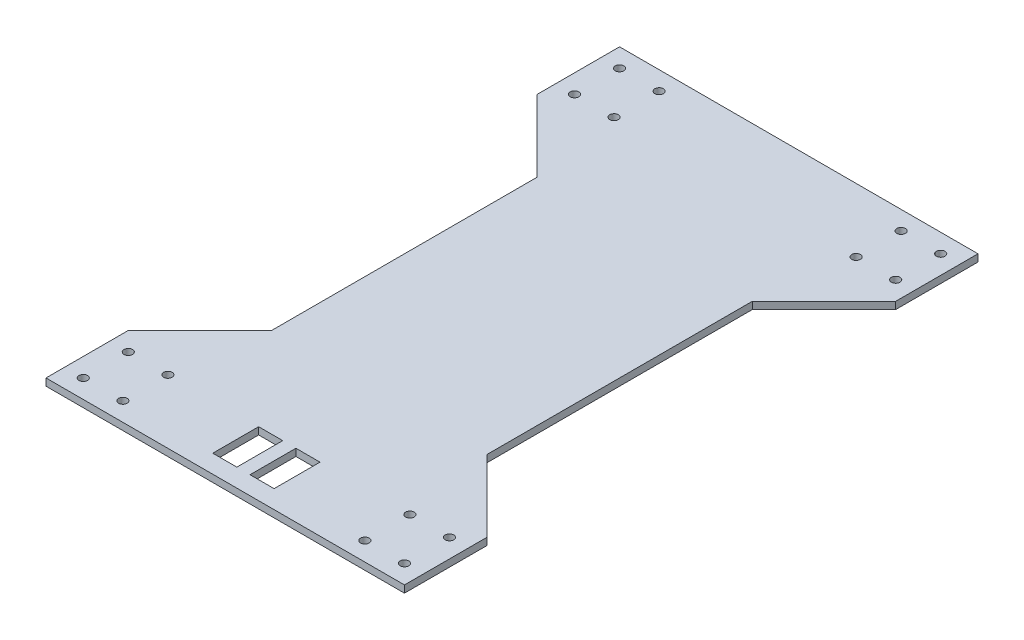
SolidWorks part; units mm, degrees
ref_plane "Alzado" through (0, 0, 0) normal (0, 0, 1) x (1, 0, 0)
ref_plane "Planta" through (0, 0, 0) normal (0, 1, 0) x (1, 0, 0)
ref_plane "Vista lateral" through (0, 0, 0) normal (1, 0, 0) x (0, 0, -1)
sketch "Sketch1" plane through (0, 0, 0) normal (0, 1, 0) x (1, 0, 0)
  line L0 (5, 200) -> (5, 0) construction
  line L5 (0, 0) -> (125, 0)
  line L6 (0, 0) -> (0, 28.7)
  line L7 (0, 200) -> (125, 200)
  line L8 (125, 0) -> (125, 28.7)
  line L9 (0, 28.7) -> (25, 53.7)
  line L10 (0, 8) -> (6.5, 8) construction
  line L11 (0, 20.7) -> (6.5, 20.7) construction
  line L12 (0, 5) -> (6.5, 5) construction
  line L13 (6.5, 22.2) -> (6.5, 6.5) construction
  line L14 (6.5, 6.5) -> (20.3, 6.5) construction
  line L15 (62.5, 200) -> (62.5, 0) construction
  line L16 (21.8, 0) -> (21.8, 200) construction
  line L17 (25, 53.7) -> (25, 146.3)
  line L18 (51.8, 22.35) -> (60.2, 22.35)
  line L19 (51.8, 22.35) -> (51.8, 6.35)
  line L20 (51.8, 6.35) -> (60.2, 6.35)
  line L21 (60.2, 22.35) -> (60.2, 6.35)
  line L22 (25, 146.3) -> (0, 171.3)
  line L23 (125, 171.3) -> (100, 146.3)
  line L24 (100, 146.3) -> (100, 53.7)
  line L25 (100, 53.7) -> (125, 28.7)
  line L26 (25, 100) -> (100, 100) construction
  line L27 (0, 23.7) -> (21.8, 23.7) construction
  line L28 (0, 171.3) -> (0, 200)
  line L29 (125, 171.3) -> (125, 200)
  line L30 (73.2, 6.35) -> (64.8, 6.35)
  line L31 (64.8, 22.35) -> (64.8, 6.35)
  line L32 (73.2, 22.35) -> (64.8, 22.35)
  line L33 (73.2, 22.35) -> (73.2, 6.35)
  line L34 (20.3, 22.2) -> (20.3, 6.5) construction
  line L35 (8, 22.2) -> (8, 23.7) construction
  line L36 (18.8, 22.2) -> (18.8, 23.7) construction
  circle A0 centre (6.5, 6.5) radius 1.5
  circle A1 centre (6.5, 22.2) radius 1.5
  circle A2 centre (20.3, 6.5) radius 1.5
  circle A3 centre (20.3, 22.2) radius 1.5
  circle A4 centre (104.7, 6.5) radius 1.5
  circle A5 centre (118.5, 6.5) radius 1.5
  circle A6 centre (104.7, 22.2) radius 1.5
  circle A7 centre (118.5, 22.2) radius 1.5
  circle A8 centre (118.5, 177.8) radius 1.5
  circle A9 centre (118.5, 193.5) radius 1.5
  circle A10 centre (104.7, 193.5) radius 1.5
  circle A11 centre (104.7, 177.8) radius 1.5
  circle A12 centre (20.3, 193.5) radius 1.5
  circle A13 centre (20.3, 177.8) radius 1.5
  circle A14 centre (6.5, 193.5) radius 1.5
  circle A15 centre (6.5, 177.8) radius 1.5
  point P34 (51.8, 14.35)
  point P40 (25, 100)
  point P41 (100, 100)
  point P73 (20.3, 14.35)
  dimension "D5" = 12.7
  dimension "D6" = 3
  dimension "D7" = 5
  dimension "D8" = 30
  dimension "D1" = 125
  dimension "D2" = 200
  dimension "D3" = 5
  dimension "D4" = 2.3
  dimension "D9" = 10.8
  dimension "D10" = 16
  dimension "D11" = 45
  dimension "D12" = 75
  dimension "D13" = 125
  dimension "D14" = 5
extrude "Boss-Extrude1" add sketch "Sketch1" along normal blind 2.5
